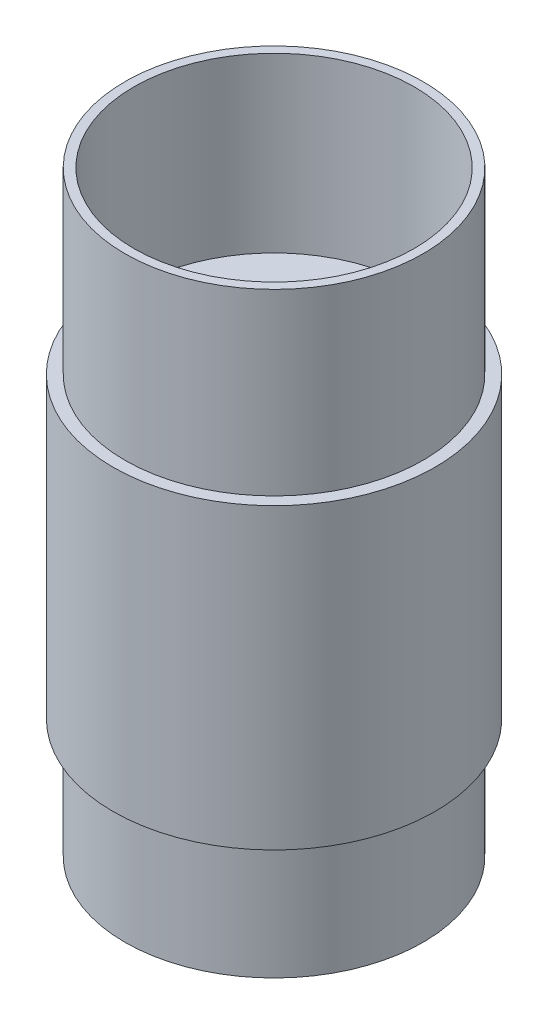
SolidWorks part; units mm, degrees
material "Balsa"
ref_plane "Plano frontal" through (0, 0, 0) normal (0, 0, 1) x (1, 0, 0)
ref_plane "Plano superior" through (0, 0, 0) normal (0, 1, 0) x (1, 0, 0)
ref_plane "Plano direito" through (0, 0, 0) normal (1, 0, 0) x (0, 0, -1)
sketch "Esboço1" plane through (0, 0, 0) normal (0, 1, 0) x (1, 0, 0)
  circle A0 centre (0, 0) radius 25
  circle A1 centre (0, 0) radius 23.5
extrude "Ressalto-extrusão1" add sketch "Esboço1" along normal blind 20 contours A1 | A0
sketch "Esboço2" plane through (0, 20, 0) normal (0, 1, 0) x (1, 0, 0)
  circle A0 centre (0, 0) radius 27
  circle A1 centre (0, 0) radius 25
extrude "Ressalto-extrusão2" add sketch "Esboço2" along normal blind 50 separate body contours A1 | A0
sketch "Esboço3" plane through (0, 70, 0) normal (0, 1, 0) x (1, 0, 0)
  circle A0 centre (0, 0) radius 23.5
  circle A1 centre (0, 0) radius 25
extrude "Ressalto-extrusão3" add sketch "Esboço3" along normal blind 30 separate body contours A1 | A0
sketch "Esboço18" plane through (0, 70, 0) normal (0, 1, 0) x (1, 0, 0)
  circle A0 centre (0, 0) radius 24
extrude "Ressalto-extrusão4" add sketch "Esboço18" along normal blind 1
